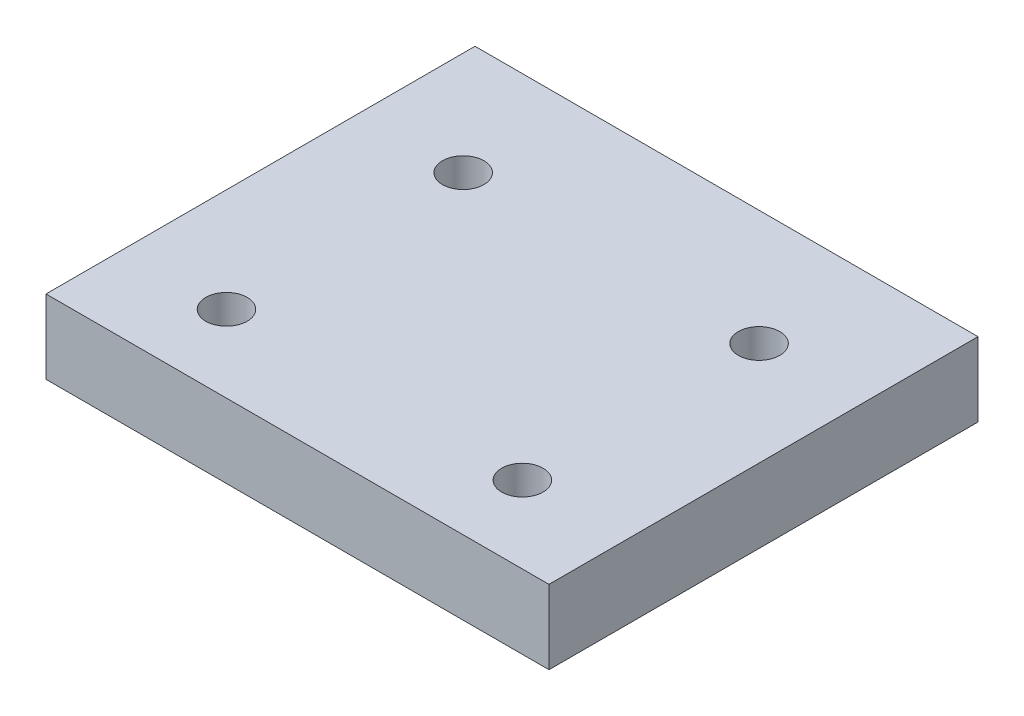
SolidWorks part; units mm, degrees
ref_plane "Front Plane" through (0, 0, 0) normal (0, 0, 1) x (1, 0, 0)
ref_plane "Top Plane" through (0, 0, 0) normal (0, 1, 0) x (1, 0, 0)
ref_plane "Right Plane" through (0, 0, 0) normal (1, 0, 0) x (0, 0, -1)
sketch "Sketch1" plane through (0, 0, 0) normal (0, 1, 0) x (1, 0, 0)
  line L1 (-17, 14.5) -> (17, 14.5)
  line L2 (-17, 14.5) -> (-17, -14.5)
  line L3 (-17, -14.5) -> (17, -14.5)
  line L4 (17, 14.5) -> (17, -14.5)
  line L5 (-17, 14.5) -> (17, -14.5) construction
  line L6 (-17, -14.5) -> (17, 14.5) construction
  circle A0 centre (-10, -9.3) radius 1.4
  circle A1 centre (10, -9.3) radius 1.4
  circle A2 centre (10, 6.7) radius 1.4
  circle A3 centre (-10, 6.7) radius 1.4
  point P0 (0, 0)
  dimension "D3" = 5.2
  dimension "D4" = 7
  dimension "D1" = 34
  dimension "D2" = 29
  dimension "D5" = 2
  dimension "D6" = 2
extrude "Boss-Extrude1" add sketch "Sketch1" along normal blind 5
